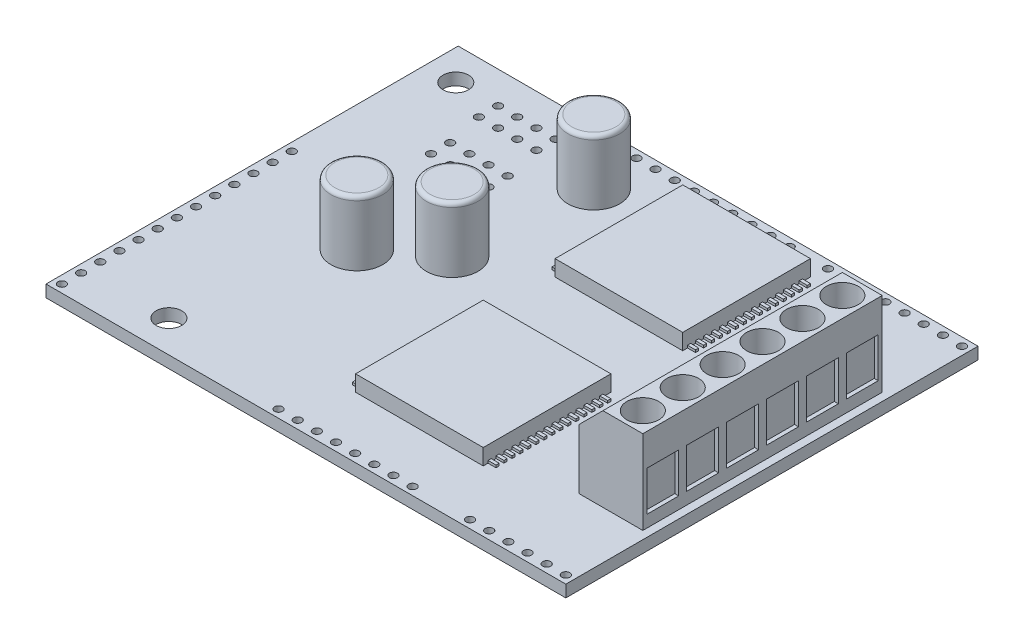
SolidWorks part; units mm, degrees
ref_plane "Спереди" through (0, 0, 0) normal (0, 0, 1) x (1, 0, 0)
ref_plane "Сверху" through (0, 0, 0) normal (0, 1, 0) x (1, 0, 0)
ref_plane "Справа" through (0, 0, 0) normal (1, 0, 0) x (0, 0, -1)
sketch "Эскиз1" plane through (0, 0, 0) normal (0, 1, 0) x (1, 0, 0)
  line L1 (-32.57, 25.825) -> (32.57, 25.825)
  line L2 (-32.57, 25.825) -> (-32.57, -25.825)
  line L3 (-32.57, -25.825) -> (32.57, -25.825)
  line L4 (32.57, 25.825) -> (32.57, -25.825)
  dimension "D1" = 65.14
  dimension "D2" = 51.65
  dimension "D3" = 32.57
  dimension "D4" = 25.825
extrude "Бобышка-Вытянуть1" add sketch "Эскиз1" along normal blind 1.5
sketch "Эскиз2" plane through (0, 1.5, 0) normal (0, 1, 0) x (1, 0, 0)
  line L0 (32.57, -25.825) -> (32.57, 25.825) construction
  line L1 (-1.43, 22.825) -> (14.57, 22.825)
  line L2 (-1.43, 22.825) -> (-1.43, 6.825)
  line L3 (-1.43, 6.825) -> (14.57, 6.825)
  line L4 (14.57, 22.825) -> (14.57, 6.825)
  line L5 (32.57, 25.825) -> (-32.57, 25.825) construction
  line L6 (-1.43, -2.175) -> (14.57, -2.175)
  line L7 (-1.43, -2.175) -> (-1.43, -18.175)
  line L8 (-1.43, -18.175) -> (14.57, -18.175)
  line L9 (14.57, -2.175) -> (14.57, -18.175)
  dimension "D1" = 16
  dimension "D2" = 16
  dimension "D3" = 18
  dimension "D4" = 3
  dimension "D5" = 2
extrude "Бобышка-Вытянуть2" add sketch "Эскиз2" along normal blind 2
sketch "Эскиз3" plane through (0, 1.5, 0) normal (0, 1, 0) x (1, 0, 0)
  line L0 (14.57, 6.825) -> (14.57, 22.825) construction
  line L1 (14.57, 21.825) -> (15.57, 21.825)
  line L2 (14.57, 21.825) -> (14.57, 21.425)
  line L3 (14.57, 21.425) -> (15.57, 21.425)
  line L4 (15.57, 21.825) -> (15.57, 21.425)
  line L5 (14.57, 22.825) -> (-1.43, 22.825) construction
  line L6 (14.57, 20.825) -> (15.57, 20.825)
  line L7 (14.57, 20.825) -> (14.57, 20.425)
  line L8 (14.57, 20.425) -> (15.57, 20.425)
  line L9 (15.57, 20.825) -> (15.57, 20.425)
  line L10 (14.57, 19.825) -> (15.57, 19.825)
  line L11 (14.57, 19.825) -> (14.57, 19.425)
  line L12 (14.57, 19.425) -> (15.57, 19.425)
  line L13 (15.57, 19.825) -> (15.57, 19.425)
  line L14 (14.57, 18.825) -> (15.57, 18.825)
  line L15 (14.57, 18.825) -> (14.57, 18.425)
  line L16 (14.57, 18.425) -> (15.57, 18.425)
  line L17 (15.57, 18.825) -> (15.57, 18.425)
  line L18 (14.57, 17.825) -> (15.57, 17.825)
  line L19 (14.57, 17.825) -> (14.57, 17.425)
  line L20 (14.57, 17.425) -> (15.57, 17.425)
  line L21 (15.57, 17.825) -> (15.57, 17.425)
  line L22 (14.57, 16.825) -> (15.57, 16.825)
  line L23 (14.57, 16.825) -> (14.57, 16.425)
  line L24 (14.57, 16.425) -> (15.57, 16.425)
  line L25 (15.57, 16.825) -> (15.57, 16.425)
  line L26 (14.57, 15.825) -> (15.57, 15.825)
  line L27 (14.57, 15.825) -> (14.57, 15.425)
  line L28 (14.57, 15.425) -> (15.57, 15.425)
  line L29 (15.57, 15.825) -> (15.57, 15.425)
  line L30 (14.57, 14.825) -> (15.57, 14.825)
  line L31 (14.57, 14.825) -> (14.57, 14.425)
  line L32 (14.57, 14.425) -> (15.57, 14.425)
  line L33 (15.57, 14.825) -> (15.57, 14.425)
  line L34 (14.57, 13.825) -> (15.57, 13.825)
  line L35 (14.57, 13.825) -> (14.57, 13.425)
  line L36 (14.57, 13.425) -> (15.57, 13.425)
  line L37 (15.57, 13.825) -> (15.57, 13.425)
  line L38 (14.57, 12.825) -> (15.57, 12.825)
  line L39 (14.57, 12.825) -> (14.57, 12.425)
  line L40 (14.57, 12.425) -> (15.57, 12.425)
  line L41 (15.57, 12.825) -> (15.57, 12.425)
  line L42 (14.57, 11.825) -> (15.57, 11.825)
  line L43 (14.57, 11.825) -> (14.57, 11.425)
  line L44 (14.57, 11.425) -> (15.57, 11.425)
  line L45 (15.57, 11.825) -> (15.57, 11.425)
  line L46 (14.57, 10.825) -> (15.57, 10.825)
  line L47 (14.57, 10.825) -> (14.57, 10.425)
  line L48 (14.57, 10.425) -> (15.57, 10.425)
  line L49 (15.57, 10.825) -> (15.57, 10.425)
  line L50 (14.57, 9.825) -> (15.57, 9.825)
  line L51 (14.57, 9.825) -> (14.57, 9.425)
  line L52 (14.57, 9.425) -> (15.57, 9.425)
  line L53 (15.57, 9.825) -> (15.57, 9.425)
  line L54 (14.57, 8.825) -> (15.57, 8.825)
  line L55 (14.57, 8.825) -> (14.57, 8.425)
  line L56 (14.57, 8.425) -> (15.57, 8.425)
  line L57 (15.57, 8.825) -> (15.57, 8.425)
  line L58 (14.57, 7.825) -> (15.57, 7.825)
  line L59 (14.57, 7.825) -> (14.57, 7.425)
  line L60 (14.57, 7.425) -> (15.57, 7.425)
  line L61 (15.57, 7.825) -> (15.57, 7.425)
  line L62 (6.57, 54.7714) -> (6.57, -83.906) construction
  line L63 (-2.43, 7.825) -> (-2.43, 7.425)
  line L64 (-1.43, 7.425) -> (-2.43, 7.425)
  line L65 (-1.43, 7.825) -> (-1.43, 7.425)
  line L66 (-1.43, 7.825) -> (-2.43, 7.825)
  line L67 (-2.43, 8.825) -> (-2.43, 8.425)
  line L68 (-1.43, 8.425) -> (-2.43, 8.425)
  line L69 (-1.43, 8.825) -> (-1.43, 8.425)
  line L70 (-1.43, 8.825) -> (-2.43, 8.825)
  line L71 (-2.43, 9.825) -> (-2.43, 9.425)
  line L72 (-1.43, 9.425) -> (-2.43, 9.425)
  line L73 (-1.43, 9.825) -> (-1.43, 9.425)
  line L74 (-1.43, 9.825) -> (-2.43, 9.825)
  line L75 (-2.43, 10.825) -> (-2.43, 10.425)
  line L76 (-1.43, 10.425) -> (-2.43, 10.425)
  line L77 (-1.43, 10.825) -> (-1.43, 10.425)
  line L78 (-1.43, 10.825) -> (-2.43, 10.825)
  line L79 (-2.43, 11.825) -> (-2.43, 11.425)
  line L80 (-1.43, 11.425) -> (-2.43, 11.425)
  line L81 (-1.43, 11.825) -> (-1.43, 11.425)
  line L82 (-1.43, 11.825) -> (-2.43, 11.825)
  line L83 (-2.43, 12.825) -> (-2.43, 12.425)
  line L84 (-1.43, 12.425) -> (-2.43, 12.425)
  line L85 (-1.43, 12.825) -> (-1.43, 12.425)
  line L86 (-1.43, 12.825) -> (-2.43, 12.825)
  line L87 (-2.43, 13.825) -> (-2.43, 13.425)
  line L88 (-1.43, 13.425) -> (-2.43, 13.425)
  line L89 (-1.43, 13.825) -> (-1.43, 13.425)
  line L90 (-1.43, 13.825) -> (-2.43, 13.825)
  line L91 (-2.43, 14.825) -> (-2.43, 14.425)
  line L92 (-1.43, 14.425) -> (-2.43, 14.425)
  line L93 (-1.43, 14.825) -> (-1.43, 14.425)
  line L94 (-1.43, 14.825) -> (-2.43, 14.825)
  line L95 (-2.43, 15.825) -> (-2.43, 15.425)
  line L96 (-1.43, 15.425) -> (-2.43, 15.425)
  line L97 (-1.43, 15.825) -> (-1.43, 15.425)
  line L98 (-1.43, 15.825) -> (-2.43, 15.825)
  line L99 (-2.43, 16.825) -> (-2.43, 16.425)
  line L100 (-1.43, 16.425) -> (-2.43, 16.425)
  line L101 (-1.43, 16.825) -> (-1.43, 16.425)
  line L102 (-1.43, 16.825) -> (-2.43, 16.825)
  line L103 (-2.43, 17.825) -> (-2.43, 17.425)
  line L104 (-1.43, 17.425) -> (-2.43, 17.425)
  line L105 (-1.43, 17.825) -> (-1.43, 17.425)
  line L106 (-1.43, 17.825) -> (-2.43, 17.825)
  line L107 (-2.43, 18.825) -> (-2.43, 18.425)
  line L108 (-1.43, 18.425) -> (-2.43, 18.425)
  line L109 (-1.43, 18.825) -> (-1.43, 18.425)
  line L110 (-1.43, 18.825) -> (-2.43, 18.825)
  line L111 (-2.43, 19.825) -> (-2.43, 19.425)
  line L112 (-1.43, 19.425) -> (-2.43, 19.425)
  line L113 (-1.43, 19.825) -> (-1.43, 19.425)
  line L114 (-1.43, 19.825) -> (-2.43, 19.825)
  line L115 (-2.43, 20.825) -> (-2.43, 20.425)
  line L116 (-1.43, 20.425) -> (-2.43, 20.425)
  line L117 (-1.43, 20.825) -> (-1.43, 20.425)
  line L118 (-1.43, 20.825) -> (-2.43, 20.825)
  line L119 (-2.43, 21.825) -> (-2.43, 21.425)
  line L120 (-1.43, 21.425) -> (-2.43, 21.425)
  line L121 (-1.43, 21.825) -> (-1.43, 21.425)
  line L122 (-1.43, 21.825) -> (-2.43, 21.825)
  line L123 (14.57, -3.175) -> (15.57, -3.175)
  line L124 (14.57, -3.175) -> (14.57, -3.575)
  line L125 (14.57, -3.575) -> (15.57, -3.575)
  line L126 (15.57, -3.175) -> (15.57, -3.575)
  line L127 (14.57, -4.175) -> (15.57, -4.175)
  line L128 (14.57, -4.175) -> (14.57, -4.575)
  line L129 (14.57, -4.575) -> (15.57, -4.575)
  line L130 (15.57, -4.175) -> (15.57, -4.575)
  line L131 (14.57, -5.175) -> (15.57, -5.175)
  line L132 (14.57, -5.175) -> (14.57, -5.575)
  line L133 (14.57, -5.575) -> (15.57, -5.575)
  line L134 (15.57, -5.175) -> (15.57, -5.575)
  line L135 (14.57, -6.175) -> (15.57, -6.175)
  line L136 (14.57, -6.175) -> (14.57, -6.575)
  line L137 (14.57, -6.575) -> (15.57, -6.575)
  line L138 (15.57, -6.175) -> (15.57, -6.575)
  line L139 (14.57, -7.175) -> (15.57, -7.175)
  line L140 (14.57, -7.175) -> (14.57, -7.575)
  line L141 (14.57, -7.575) -> (15.57, -7.575)
  line L142 (15.57, -7.175) -> (15.57, -7.575)
  line L143 (14.57, -8.175) -> (15.57, -8.175)
  line L144 (14.57, -8.175) -> (14.57, -8.575)
  line L145 (14.57, -8.575) -> (15.57, -8.575)
  line L146 (15.57, -8.175) -> (15.57, -8.575)
  line L147 (14.57, -9.175) -> (15.57, -9.175)
  line L148 (14.57, -9.175) -> (14.57, -9.575)
  line L149 (14.57, -9.575) -> (15.57, -9.575)
  line L150 (15.57, -9.175) -> (15.57, -9.575)
  line L151 (14.57, -10.175) -> (15.57, -10.175)
  line L152 (14.57, -10.175) -> (14.57, -10.575)
  line L153 (14.57, -10.575) -> (15.57, -10.575)
  line L154 (15.57, -10.175) -> (15.57, -10.575)
  line L155 (14.57, -11.175) -> (15.57, -11.175)
  line L156 (14.57, -11.175) -> (14.57, -11.575)
  line L157 (14.57, -11.575) -> (15.57, -11.575)
  line L158 (15.57, -11.175) -> (15.57, -11.575)
  line L159 (14.57, -12.175) -> (15.57, -12.175)
  line L160 (14.57, -12.175) -> (14.57, -12.575)
  line L161 (14.57, -12.575) -> (15.57, -12.575)
  line L162 (15.57, -12.175) -> (15.57, -12.575)
  line L163 (14.57, -13.175) -> (15.57, -13.175)
  line L164 (14.57, -13.175) -> (14.57, -13.575)
  line L165 (14.57, -13.575) -> (15.57, -13.575)
  line L166 (15.57, -13.175) -> (15.57, -13.575)
  line L167 (14.57, -14.175) -> (15.57, -14.175)
  line L168 (14.57, -14.175) -> (14.57, -14.575)
  line L169 (14.57, -14.575) -> (15.57, -14.575)
  line L170 (15.57, -14.175) -> (15.57, -14.575)
  line L171 (14.57, -15.175) -> (15.57, -15.175)
  line L172 (14.57, -15.175) -> (14.57, -15.575)
  line L173 (14.57, -15.575) -> (15.57, -15.575)
  line L174 (15.57, -15.175) -> (15.57, -15.575)
  line L175 (14.57, -16.175) -> (15.57, -16.175)
  line L176 (14.57, -16.175) -> (14.57, -16.575)
  line L177 (14.57, -16.575) -> (15.57, -16.575)
  line L178 (15.57, -16.175) -> (15.57, -16.575)
  line L179 (14.57, -17.175) -> (15.57, -17.175)
  line L180 (14.57, -17.175) -> (14.57, -17.575)
  line L181 (14.57, -17.575) -> (15.57, -17.575)
  line L182 (15.57, -17.175) -> (15.57, -17.575)
  line L183 (-2.43, -17.175) -> (-2.43, -17.575)
  line L184 (-1.43, -17.575) -> (-2.43, -17.575)
  line L185 (-1.43, -17.175) -> (-1.43, -17.575)
  line L186 (-1.43, -17.175) -> (-2.43, -17.175)
  line L187 (-2.43, -16.175) -> (-2.43, -16.575)
  line L188 (-1.43, -16.575) -> (-2.43, -16.575)
  line L189 (-1.43, -16.175) -> (-1.43, -16.575)
  line L190 (-1.43, -16.175) -> (-2.43, -16.175)
  line L191 (-2.43, -15.175) -> (-2.43, -15.575)
  line L192 (-1.43, -15.575) -> (-2.43, -15.575)
  line L193 (-1.43, -15.175) -> (-1.43, -15.575)
  line L194 (-1.43, -15.175) -> (-2.43, -15.175)
  line L195 (-2.43, -14.175) -> (-2.43, -14.575)
  line L196 (-1.43, -14.575) -> (-2.43, -14.575)
  line L197 (-1.43, -14.175) -> (-1.43, -14.575)
  line L198 (-1.43, -14.175) -> (-2.43, -14.175)
  line L199 (-2.43, -13.175) -> (-2.43, -13.575)
  line L200 (-1.43, -13.575) -> (-2.43, -13.575)
  line L201 (-1.43, -13.175) -> (-1.43, -13.575)
  line L202 (-1.43, -13.175) -> (-2.43, -13.175)
  line L203 (-2.43, -12.175) -> (-2.43, -12.575)
  line L204 (-1.43, -12.575) -> (-2.43, -12.575)
  line L205 (-1.43, -12.175) -> (-1.43, -12.575)
  line L206 (-1.43, -12.175) -> (-2.43, -12.175)
  line L207 (-2.43, -11.175) -> (-2.43, -11.575)
  line L208 (-1.43, -11.575) -> (-2.43, -11.575)
  line L209 (-1.43, -11.175) -> (-1.43, -11.575)
  line L210 (-1.43, -11.175) -> (-2.43, -11.175)
  line L211 (-2.43, -10.175) -> (-2.43, -10.575)
  line L212 (-1.43, -10.575) -> (-2.43, -10.575)
  line L213 (-1.43, -10.175) -> (-1.43, -10.575)
  line L214 (-1.43, -10.175) -> (-2.43, -10.175)
  line L215 (-2.43, -9.175) -> (-2.43, -9.575)
  line L216 (-1.43, -9.575) -> (-2.43, -9.575)
  line L217 (-1.43, -9.175) -> (-1.43, -9.575)
  line L218 (-1.43, -9.175) -> (-2.43, -9.175)
  line L219 (-2.43, -8.175) -> (-2.43, -8.575)
  line L220 (-1.43, -8.575) -> (-2.43, -8.575)
  line L221 (-1.43, -8.175) -> (-1.43, -8.575)
  line L222 (-1.43, -8.175) -> (-2.43, -8.175)
  line L223 (-2.43, -7.175) -> (-2.43, -7.575)
  line L224 (-1.43, -7.575) -> (-2.43, -7.575)
  line L225 (-1.43, -7.175) -> (-1.43, -7.575)
  line L226 (-1.43, -7.175) -> (-2.43, -7.175)
  line L227 (-2.43, -6.175) -> (-2.43, -6.575)
  line L228 (-1.43, -6.575) -> (-2.43, -6.575)
  line L229 (-1.43, -6.175) -> (-1.43, -6.575)
  line L230 (-1.43, -6.175) -> (-2.43, -6.175)
  line L231 (-2.43, -5.175) -> (-2.43, -5.575)
  line L232 (-1.43, -5.575) -> (-2.43, -5.575)
  line L233 (-1.43, -5.175) -> (-1.43, -5.575)
  line L234 (-1.43, -5.175) -> (-2.43, -5.175)
  line L235 (-2.43, -4.175) -> (-2.43, -4.575)
  line L236 (-1.43, -4.575) -> (-2.43, -4.575)
  line L237 (-1.43, -4.175) -> (-1.43, -4.575)
  line L238 (-1.43, -4.175) -> (-2.43, -4.175)
  line L239 (-2.43, -3.175) -> (-2.43, -3.575)
  line L240 (-1.43, -3.575) -> (-2.43, -3.575)
  line L241 (-1.43, -3.175) -> (-1.43, -3.575)
  line L242 (-1.43, -3.175) -> (-2.43, -3.175)
  dimension "D1" = 0.4
  dimension "D2" = 1
  dimension "D3" = 1
  dimension "D5" = 8
  dimension "D6" = 8
  dimension "D4" = 15
  dimension "D7" = 2
extrude "Бобышка-Вытянуть3" add sketch "Эскиз3" along normal blind 0.3
sketch "Эскиз4" plane through (0, 1.5, 0) normal (0, 1, 0) x (1, 0, 0)
  line L0 (32.57, -25.825) -> (32.57, 25.825) construction
  line L1 (-32.57, -25.825) -> (32.57, -25.825) construction
  line L2 (32.57, 25.825) -> (-32.57, 25.825) construction
  line L3 (-32.57, 25.825) -> (-32.57, -25.825) construction
  circle A0 centre (31.57, -24.825) radius 0.5
  circle A1 centre (29.17, -24.825) radius 0.5
  circle A2 centre (26.77, -24.825) radius 0.5
  circle A3 centre (24.37, -24.825) radius 0.5
  circle A4 centre (21.97, -24.825) radius 0.5
  circle A5 centre (19.57, -24.825) radius 0.5
  circle A6 centre (31.57, 24.825) radius 0.5
  circle A7 centre (29.17, 24.825) radius 0.5
  circle A8 centre (12.37, -24.825) radius 0.5
  circle A9 centre (9.97, -24.825) radius 0.5
  circle A10 centre (7.57, -24.825) radius 0.5
  circle A11 centre (5.17, -24.825) radius 0.5
  circle A12 centre (2.77, -24.825) radius 0.5
  circle A13 centre (0.37, -24.825) radius 0.5
  circle A14 centre (-2.03, -24.825) radius 0.5
  circle A15 centre (-4.43, -24.825) radius 0.5
  circle A16 centre (17.17, -24.825) radius 0.5 [skipped]
  circle A17 centre (14.77, -24.825) radius 0.5 [skipped]
  circle A18 centre (26.77, 24.825) radius 0.5
  circle A19 centre (24.37, 24.825) radius 0.5
  circle A20 centre (21.97, 24.825) radius 0.5
  circle A21 centre (19.57, 24.825) radius 0.5
  circle A22 centre (17.17, 24.825) radius 0.5
  circle A23 centre (14.77, 24.825) radius 0.5
  circle A24 centre (-31.57, -24.825) radius 0.5
  circle A25 centre (9.97, 24.825) radius 0.5
  circle A26 centre (7.57, 24.825) radius 0.5
  circle A27 centre (5.17, 24.825) radius 0.5
  circle A28 centre (2.77, 24.825) radius 0.5
  circle A29 centre (0.37, 24.825) radius 0.5
  circle A30 centre (-2.03, 24.825) radius 0.5
  circle A31 centre (-4.43, 24.825) radius 0.5
  circle A32 centre (-6.83, 24.825) radius 0.5
  circle A33 centre (-9.23, 24.825) radius 0.5
  circle A34 centre (-11.63, 24.825) radius 0.5
  circle A35 centre (12.37, 24.825) radius 0.5 [skipped]
  circle A36 centre (-31.57, -22.425) radius 0.5
  circle A37 centre (-31.57, -20.025) radius 0.5
  circle A38 centre (-31.57, -17.625) radius 0.5
  circle A39 centre (-31.57, -15.225) radius 0.5
  circle A40 centre (-31.57, -12.825) radius 0.5
  circle A41 centre (-31.57, -10.425) radius 0.5
  circle A42 centre (-31.57, -8.025) radius 0.5
  circle A43 centre (-31.57, -5.625) radius 0.5
  circle A44 centre (-31.57, -3.225) radius 0.5
  circle A45 centre (-31.57, -0.825) radius 0.5
  circle A46 centre (-31.57, 1.575) radius 0.5
  circle A47 centre (-31.57, 3.975) radius 0.5
  circle A48 centre (-28.77, 21.725) radius 1.6
  circle A49 centre (-21.17, -21.825) radius 1.6
  circle A50 centre (-23.57, 21.825) radius 0.5
  circle A51 centre (-21.17, 21.825) radius 0.5
  circle A52 centre (-18.77, 21.825) radius 0.5
  circle A53 centre (-16.37, 21.825) radius 0.5
  circle A54 centre (-21.17, 19.425) radius 0.5
  circle A55 centre (-18.77, 19.425) radius 0.5
  circle A56 centre (-16.37, 19.425) radius 0.5
  circle A57 centre (-23.57, 19.425) radius 0.5
  circle A58 centre (-22.57, 14.825) radius 0.5
  circle A59 centre (-20.17, 14.825) radius 0.5
  circle A60 centre (-17.77, 14.825) radius 0.5
  circle A61 centre (-15.37, 14.825) radius 0.5
  circle A62 centre (-20.17, 12.425) radius 0.5
  circle A63 centre (-17.77, 12.425) radius 0.5
  circle A64 centre (-15.37, 12.425) radius 0.5
  circle A65 centre (-22.57, 12.425) radius 0.5
  dimension "D1" = 1
  dimension "D5" = 1
  dimension "D9" = 1
  dimension "D12" = 13
  dimension "D13" = 3.2
  dimension "D16" = 3.2
  dimension "D19" = 1
  dimension "D2" = 1
  dimension "D3" = 1
  dimension "D6" = 1
  dimension "D7" = 1
  dimension "D10" = 1
  dimension "D11" = 1
  dimension "D14" = 4.1
  dimension "D15" = 3.8
  dimension "D17" = 4
  dimension "D18" = 11.4
  dimension "D20" = 4
  dimension "D21" = 9
  dimension "D24" = 10
  dimension "D25" = 11
  dimension "D4" = 16
  dimension "D8" = 19
  dimension "D22" = 4
  dimension "D23" = 2
  dimension "D26" = 4
  dimension "D27" = 2
extrude "Вырез-Вытянуть1" cut sketch "Эскиз4" against normal blind 2
sketch "Эскиз5" plane through (0, 1.5, 0) normal (0, 1, 0) x (1, 0, 0)
  line L1 (23.57, 14.825) -> (31.57, 14.825)
  line L2 (23.57, 14.825) -> (23.57, -15.175)
  line L3 (23.57, -15.175) -> (31.57, -15.175)
  line L4 (31.57, 14.825) -> (31.57, -15.175)
  dimension "D1" = 30
  dimension "D2" = 8
  dimension "D3" = 11
  dimension "D4" = 1
extrude "Бобышка-Вытянуть4" add sketch "Эскиз5" along normal blind 10.5
chamfer "Фаска1" distance 3 angle 45 1 edges at (23.57, 12, 0.175)
sketch "Эскиз6" plane through (0, 12, 0) normal (0, 1, 0) x (1, 0, 0)
  line L0 (31.57, 14.825) -> (23.57, 14.825) construction
  line L1 (31.57, -15.175) -> (31.57, 14.825) construction
  circle A0 centre (29.0693, 12.325) radius 2
  circle A1 centre (29.0693, 7.325) radius 2
  circle A2 centre (29.0693, 2.325) radius 2
  circle A3 centre (29.0693, -2.675) radius 2
  circle A4 centre (29.0693, -7.675) radius 2
  circle A5 centre (29.0693, -12.675) radius 2
  dimension "D1" = 4
  dimension "D2" = 2.5
  dimension "D3" = 2.5007
  dimension "D4" = 6
extrude "Вырез-Вытянуть2" cut sketch "Эскиз6" against normal blind 4
sketch "Эскиз7" plane through (31.57, 0, 0) normal (1, 0, 0) x (0, 0, -1)
  line L0 (14.825, 12) -> (14.825, 1.5) construction
  line L1 (14.325, 8) -> (10.325, 8)
  line L2 (14.325, 8) -> (14.325, 3)
  line L3 (14.325, 3) -> (10.325, 3)
  line L4 (10.325, 8) -> (10.325, 3)
  line L5 (-15.175, 1.5) -> (14.825, 1.5) construction
  line L6 (9.325, 8) -> (5.325, 8)
  line L7 (9.325, 8) -> (9.325, 3)
  line L8 (9.325, 3) -> (5.325, 3)
  line L9 (5.325, 8) -> (5.325, 3)
  line L10 (4.325, 8) -> (0.325, 8)
  line L11 (4.325, 8) -> (4.325, 3)
  line L12 (4.325, 3) -> (0.325, 3)
  line L13 (0.325, 8) -> (0.325, 3)
  line L14 (-0.675, 8) -> (-4.675, 8)
  line L15 (-0.675, 8) -> (-0.675, 3)
  line L16 (-0.675, 3) -> (-4.675, 3)
  line L17 (-4.675, 8) -> (-4.675, 3)
  line L18 (-5.675, 8) -> (-9.675, 8)
  line L19 (-5.675, 8) -> (-5.675, 3)
  line L20 (-5.675, 3) -> (-9.675, 3)
  line L21 (-9.675, 8) -> (-9.675, 3)
  line L22 (-10.675, 8) -> (-14.675, 8)
  line L23 (-10.675, 8) -> (-10.675, 3)
  line L24 (-10.675, 3) -> (-14.675, 3)
  line L25 (-14.675, 8) -> (-14.675, 3)
  dimension "D1" = 4
  dimension "D2" = 0.5
  dimension "D3" = 1.5
  dimension "D4" = 5
  dimension "D5" = 6
extrude "Вырез-Вытянуть3" cut sketch "Эскиз7" against normal blind 0.5
sketch "Эскиз8" plane through (7.285, -7.285, 0) normal (-0.7071, 0.7071, 0) x (0, 0, 1)
  line L0 (-14.825, 23.0305) -> (-14.825, 27.2731) construction
  line L1 (15.175, 23.0305) -> (-14.825, 23.0305) construction
  circle A0 centre (-12.325, 25.0305) radius 0.5
  circle A1 centre (-7.325, 25.0305) radius 0.5
  circle A2 centre (-2.325, 25.0305) radius 0.5
  circle A3 centre (2.675, 25.0305) radius 0.5
  circle A4 centre (7.675, 25.0305) radius 0.5
  circle A5 centre (12.675, 25.0305) radius 0.5
  point P2 (-14.825, 25.1518)
  dimension "D1" = 1
  dimension "D2" = 2.5
  dimension "D3" = 2
  dimension "D4" = 6
extrude "Вырез-Вытянуть4" cut sketch "Эскиз8" against normal blind 0.2
sketch "Эскиз9" plane through (0, 1.5, 0) normal (0, 1, 0) x (1, 0, 0)
  line L0 (-32.57, 25.825) -> (-32.57, -25.825) construction
  line L1 (32.57, 25.825) -> (-32.57, 25.825) construction
  circle A0 centre (-8.57, 18.825) radius 3.25
  circle A1 centre (-16.82, -2.625) radius 3.25
  circle A2 centre (-10.12, 2.625) radius 3.25
  dimension "D1" = 6.5
  dimension "D8" = 6.5
  dimension "D9" = 6.5
  dimension "D2" = 24
  dimension "D3" = 7
  dimension "D4" = 22.45
  dimension "D5" = 23.2
  dimension "D6" = 15.75
  dimension "D7" = 28.45
extrude "Бобышка-Вытянуть5" add sketch "Эскиз9" along normal blind 8.1
fillet "Скругление1" radius 0.5 3 edges at (-16.82, 9.6, 5.875) (-10.12, 9.6, 0.625) (-8.57, 9.6, -15.575)
